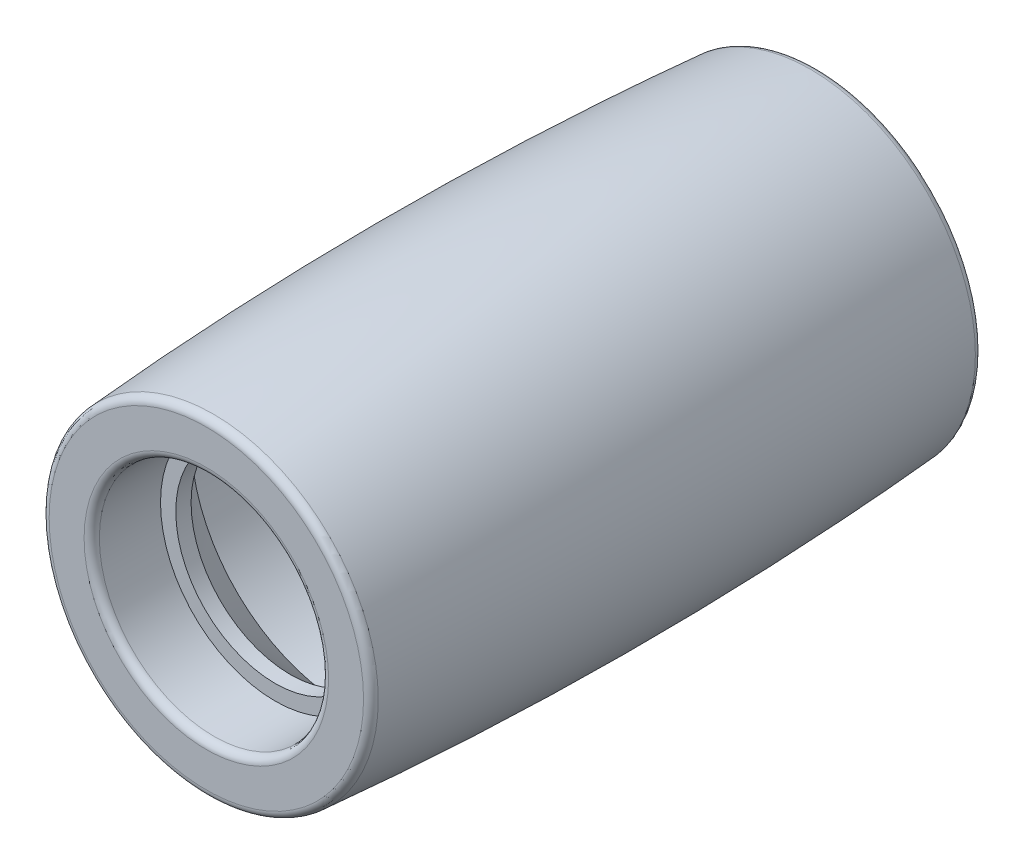
SolidWorks part; units mm, degrees
ref_plane "Ebene vorne" through (0, 0, 0) normal (0, 0, 1) x (1, 0, 0)
ref_plane "Ebene oben" through (0, 0, 0) normal (0, 1, 0) x (1, 0, 0)
ref_plane "Ebene rechts" through (0, 0, 0) normal (1, 0, 0) x (0, 0, -1)
sketch "Skizze1" plane through (450, 0, 0) normal (1, 0, 0) x (0, 0, -1)
  line L7 (20.5, 20.2121) -> (49.5, 20.2121) construction
  line L16 (49.5, 23) -> (49.5, 20.2121) construction
  line L17 (9.5, 21.5) -> (9.5, 15) construction
  line L18 (18.5, 15) -> (9.5, 15) construction
  line L19 (18.5, 15) -> (18.5, 5) construction
  line L20 (18.5, 13) -> (20.5, 13) construction
  line L21 (20.5, 13) -> (27.7121, 20.2121) construction
  line L22 (0, 0) -> (99, 0) construction
  line L23 (27.7121, 20.2121) -> (49.5, 20.2121)
  line L24 (49.5, 23) -> (49.5, 20.2121)
  line L25 (9.5, 21.5) -> (9.5, 15)
  line L26 (18.5, 15) -> (9.5, 15)
  line L27 (18.5, 15) -> (18.5, 13)
  line L28 (18.5, 13) -> (20.5, 13)
  line L29 (20.5, 13) -> (27.7121, 20.2121)
  line L30 (0, 0) -> (99, 0) construction
  arc A2 (89.5, 21.5) -> (9.5, 21.5) centre (49.5, -511.0833) ccw construction
  arc A3 (49.5, 23) -> (9.5, 21.5) centre (49.5, -511.0833) ccw
revolve "Rotation1" add sketch "Skizze1" angle 360 about L30
mirror "Spiegeln1" about plane through (450, 23, -49.5) normal (0, 0, 1) of bodies 101
fillet "Verrundung1" radius 1 4 edges at (471.5, 0, -9.5) (465, 0, -9.5) (465, 0, -89.5) (471.5, 0, -89.5)
